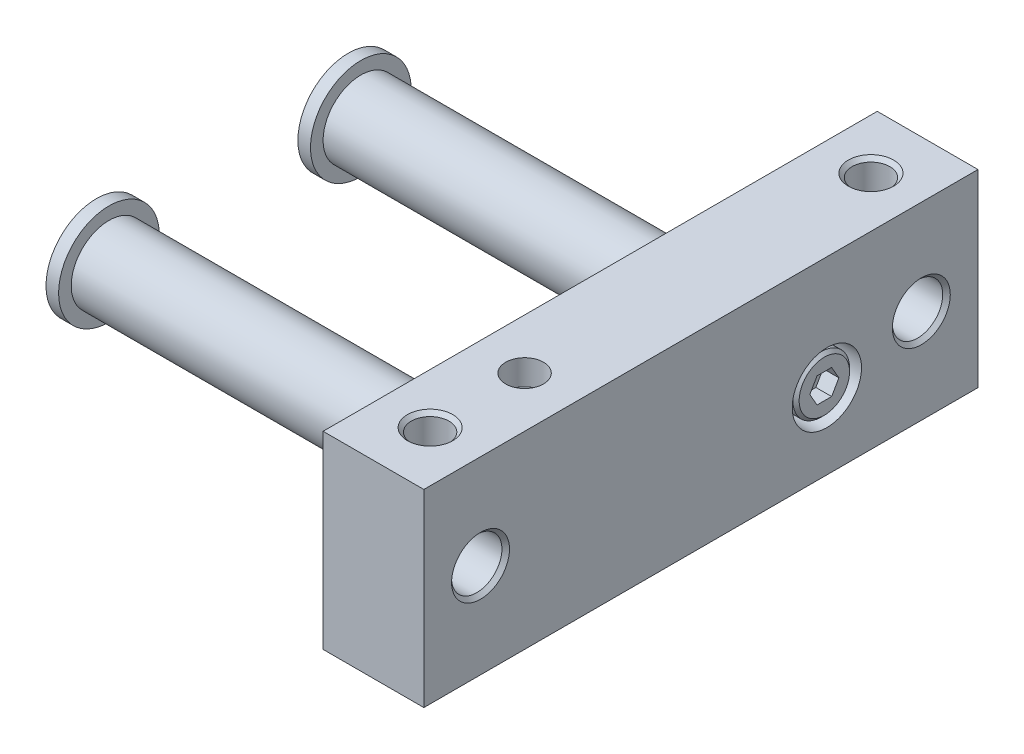
SolidWorks part; units mm, degrees
ref_plane "Plane1" through (0, 0, 0) normal (0, 0, 1) x (1, 0, 0)
ref_plane "Plane2" through (0, 0, 0) normal (0, 1, 0) x (1, 0, 0)
ref_plane "Plane3" through (0, 0, 0) normal (1, 0, 0) x (0, 0, -1)
sketch "Plate_Sketch" plane through (0, 0, 0) normal (1, 0, 0) x (0, 0, -1)
  line L0 (-22, 7.5) -> (-22, -7.5)
  line L1 (-22, -7.5) -> (22, -7.5)
  line L2 (22, -7.5) -> (22, 7.5)
  line L3 (22, 7.5) -> (-22, 7.5)
  line L4 (-24.2, 0) -> (24.2, 0) construction
  line L5 (0, -6.75) -> (0, 9.75) construction
  line L6 (0, 12.5779) -> (0, -12.5779) construction
  line L7 (16.4357, 0) -> (-16.4357, 0) construction
  dimension "C" = 44
  dimension "D" = 15
extrude "Plate" add sketch "Plate_Sketch" along normal blind 8
hole_wizard "Tapped Hole Face" positions "Tapped Hole Face Loc" profile "Tapped Hole Face Profile" tap size "M3x0.5" standard "Ansi Metric" end condition through all
sketch "Tapped Hole Face Loc" plane through (8, 0, 0) normal (1, 0, 0) x (0, 0, -1)
  line L0 (0, 0) -> (0, 21.0226) construction
  line L1 (-22, -7.5) -> (22, -7.5) construction
  point P0 (-17.5, 0)
  point P1 (17.5, 0)
  dimension "G" = 35
  dimension "E" = 7.5
sketch "Tapped Hole Face Profile" plane through (8, 0, 17.5) normal (0, 1, 0) x (0, 0, -1)
  line L0 (0, 0) -> (0, 8)
  line L1 (0, 8) -> (2, 8)
  line L2 (2, 8) -> (2, 0.3)
  line L3 (2, 0.3) -> (2.3, 0)
  line L5 (2.3, 0) -> (0, 0)
  line L6 (-2, 0.3) -> (-2.3, 0) construction
  line L11 (0, -6.35) -> (0, 107.95) construction
  dimension "Thread Major Dia." = 4
  dimension "Thru Tap Drill Depth" = 8
  dimension "Near CSink Dia." = 4.6
  dimension "Near CSink Angle" = 90
ref_plane "bottom" through (0, -8.5, 0) normal (0, -1, 0) x (1, 0, 0)
ref_plane "innerlimit" through (-9, 0, 0) normal (1, 0, 0) x (0, 0, -1)
ref_plane "strokelimit" through (-19, 0, 0) normal (1, 0, 0) x (0, 0, -1)
sketch "Rods_Sketch" plane through (-9, 0, 0) normal (-1, 0, 0) x (0, 0, 1)
  line L0 (0, -7.7893) -> (0, 7.4105) construction
  line L1 (0, -12.5779) -> (0, 12.5779) construction
  line L3 (-4, -8.5) -> (4, -8.5) construction
  circle A0 centre (-10, -1.5) radius 3
  circle A1 centre (10, -1.5) radius 3
  dimension "NN" = 6
  dimension "H" = 20
  dimension "QQ" = 7
extrude "Rods" add sketch "Rods_Sketch" along normal blind 20 and the other way up to surface (17 mm away)
sketch "Piston_Sketch" plane through (-29, 0, 0) normal (-1, 0, 0) x (0, 0, 1)
  circle A0 centre (-10, -1.5) radius 4
  circle A1 centre (10, -1.5) radius 4
extrude "Piston" add sketch "Piston_Sketch" along normal blind 1
hole_wizard "Tapped Holes Top" positions "Tapped Holes Top Loc" profile "Tapped Holes Top Profile" tap size "M3x0.5" standard "Ansi Metric"
sketch "Tapped Holes Top Loc" plane through (0, 7.5, 0) normal (0, 1, 0) x (-1, 0, 0)
  line L0 (0, 0) -> (-11.3574, 0) construction
  line L2 (-8, -22) -> (-8, 22) construction
  line L3 (0, -17.5) -> (-7.7, -17.5) construction
  point P0 (-4, -17.5)
  point P1 (-4, 17.5)
  dimension "I" = 4
sketch "Tapped Holes Top Profile" plane through (4, 7.5, -17.5) normal (1, 0, 0) x (0, 0, 1)
  line L0 (0, 0) -> (0, 5.4204)
  line L1 (0, 5.4204) -> (1.25, 5.2)
  line L2 (1.25, 5.2) -> (1.25, 5)
  line L3 (1.25, 5) -> (1.5, 5)
  line L5 (1.5, 5) -> (1.5, 0.3)
  line L6 (1.5, 0.3) -> (1.8, 0)
  line L7 (1.8, 0) -> (0, 0)
  line L8 (-1.5, 0.3) -> (-1.8, 0) construction
  line L10 (0, 5.4204) -> (-1.25, 5.2) construction
  line L11 (0, -6.35) -> (0, 107.95) construction
  dimension "Tap Drill Dia." = 2.5
  dimension "Tap Drill Depth" = 5.2
  dimension "Thread Major Dia." = 3
  dimension "Thread Depth" = 5
  dimension "Near C'Sink Dia." = 3.6
  dimension "Near C'Sink Angle" = 90
  dimension "Drill Angle" = 160
mirror "Tapped Holes Top Mirror" about plane through (0, 0, 0) normal (0, 1, 0) of "Tapped Holes Top"
sketch "SHCS Seat_Sketch" plane through (8, 0, 0) normal (1, 0, 0) x (0, 0, -1)
  circle A0 centre (10, -1.5) radius 2.75
  circle A1 centre (10, -1.5) radius 3 construction
  dimension "Dia" = 5.5
extrude "SHCS Seat" cut sketch "SHCS Seat_Sketch" against normal blind 2.7
sketch "SHCS Head_Sketch" plane through (5.3, 0, 0) normal (1, 0, 0) x (0, 0, -1)
  circle A0 centre (10, -1.5) radius 2.25
  circle A1 centre (10, -1.5) radius 2.75 construction
  dimension "Dia" = 4.5
extrude "SHCS Head" add sketch "SHCS Head_Sketch" along normal blind 2.5
sketch "SHCS Hex_Sketch" plane through (7.8, 0, 0) normal (1, 0, 0) x (0, 0, -1)
  line L1 (10.5774, -2.5) -> (11.1547, -1.5)
  line L2 (11.1547, -1.5) -> (10.5774, -0.5)
  line L3 (10.5774, -0.5) -> (9.4226, -0.5)
  line L4 (9.4226, -0.5) -> (8.8453, -1.5)
  line L5 (8.8453, -1.5) -> (9.4226, -2.5)
  line L6 (9.4226, -2.5) -> (10.5774, -2.5)
  circle A0 centre (10, -1.5) radius 1 construction
  circle A1 centre (10, -1.5) radius 2.25 construction
  dimension "Flats" = 2
extrude "SHCS Hex" cut sketch "SHCS Hex_Sketch" against normal blind 1.25
chamfer "SHCS Cham" distance 0.25 1 edges at (7.8, -1.5, -12.25)
sketch "SS Seat_Sketch" plane through (0, 7.5, 0) normal (0, 1, 0) x (-1, 0, 0)
  line L0 (29, 10) -> (0, 10) construction
  circle A0 centre (-4, 10) radius 1.5
  dimension "Dia" = 3
extrude "SS Seat" cut sketch "SS Seat_Sketch" against normal blind 2
sketch "SS Hex_Sketch" plane through (0, 5.5, 0) normal (0, 1, 0) x (-1, 0, 0)
  line L1 (-4.75, 9.567) -> (-4, 9.134)
  line L2 (-4, 9.134) -> (-3.25, 9.567)
  line L3 (-3.25, 9.567) -> (-3.25, 10.433)
  line L4 (-3.25, 10.433) -> (-4, 10.866)
  line L5 (-4, 10.866) -> (-4.75, 10.433)
  line L6 (-4.75, 10.433) -> (-4.75, 9.567)
  circle A0 centre (-4, 10) radius 0.75 construction
  circle A1 centre (-4, 10) radius 1.5 construction
  dimension "Flats" = 1.5
extrude "SS Hex" cut sketch "SS Hex_Sketch" against normal blind 1.25
